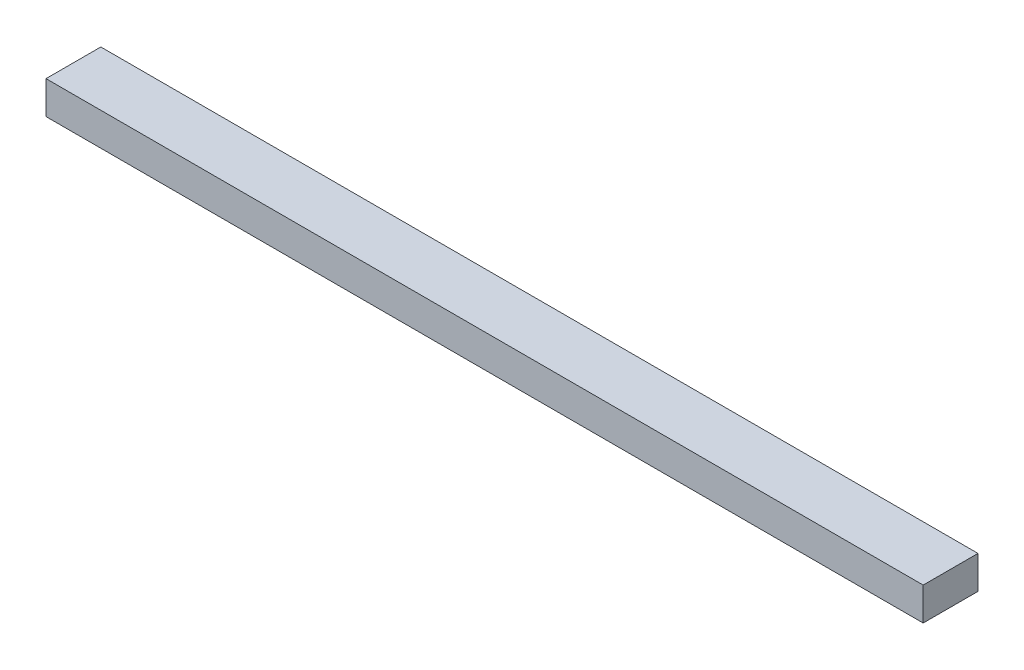
SolidWorks part; units mm, degrees
ref_plane "前视基准面" through (0, 0, 0) normal (0, 0, 1) x (1, 0, 0)
ref_plane "上视基准面" through (0, 0, 0) normal (0, 1, 0) x (1, 0, 0)
ref_plane "右视基准面" through (0, 0, 0) normal (1, 0, 0) x (0, 0, -1)
sketch "草图1" plane through (0, 0, 0) normal (0, 0, 1) x (1, 0, 0)
  line L1 (-2.875, 0.4375) -> (77.125, 0.4375)
  line L2 (-2.875, 0.4375) -> (-2.875, -2.5625)
  line L3 (-2.875, -2.5625) -> (77.125, -2.5625)
  line L4 (77.125, 0.4375) -> (77.125, -2.5625)
  dimension "D1" = 80
  dimension "D2" = 3
extrude "凸台-拉伸1" add sketch "草图1" along normal blind 5
